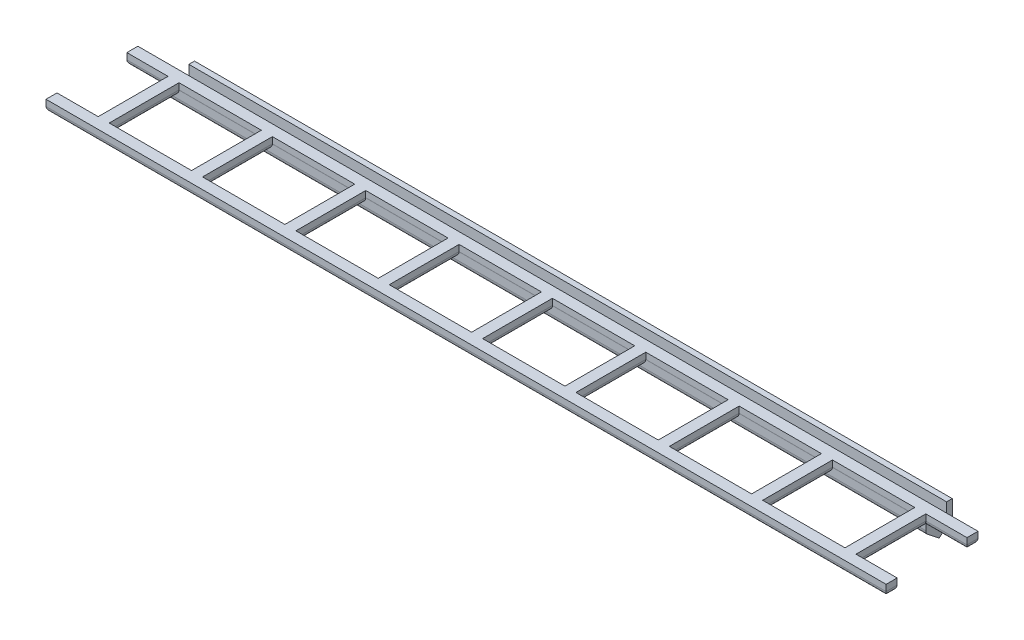
SolidWorks part; units mm, degrees
ref_plane "Front Plane" through (0, 0, 0) normal (0, 0, 1) x (1, 0, 0)
ref_plane "Top Plane" through (0, 0, 0) normal (0, 1, 0) x (1, 0, 0)
ref_plane "Right Plane" through (0, 0, 0) normal (1, 0, 0) x (0, 0, -1)
sketch "Sketch1" plane through (0, 0, 0) normal (0, 1, 0) x (1, 0, 0)
  line L0 (23.5071, 1.4357) -> (23.5071, 4.4357)
  line L1 (12.3071, 1.4357) -> (23.5071, 1.4357)
  line L2 (-1.8929, -17.5643) -> (-1.8929, -20.5643)
  line L3 (9.3071, -17.5643) -> (-1.8929, -17.5643)
  line L4 (12.3071, -17.5643) -> (23.5071, -17.5643)
  line L5 (23.5071, -17.5643) -> (23.5071, -20.5643)
  line L6 (12.3071, 1.4357) -> (12.3071, -17.5643)
  line L7 (9.3071, -17.5643) -> (9.3071, 1.4357)
  line L8 (-1.8929, 4.4357) -> (23.5071, 4.4357)
  line L9 (23.5071, -20.5643) -> (-1.8929, -20.5643)
  line L10 (9.3071, 1.4357) -> (-1.8929, 1.4357)
  line L11 (-1.8929, 1.4357) -> (-1.8929, 4.4357)
  line L12 (48.9071, 1.4357) -> (48.9071, 4.4357)
  line L13 (10.8071, 0) -> (10.8071, 1.5197) construction
  line L14 (0, -8.0643) -> (-1.4046, -8.0643) construction
  line L15 (37.7071, 1.4357) -> (48.9071, 1.4357)
  line L16 (23.5071, -17.5643) -> (23.5071, -20.5643)
  line L17 (34.7071, -17.5643) -> (23.5071, -17.5643)
  line L18 (37.7071, -17.5643) -> (48.9071, -17.5643)
  line L19 (48.9071, -17.5643) -> (48.9071, -20.5643)
  line L20 (37.7071, 1.4357) -> (37.7071, -17.5643)
  line L21 (34.7071, -17.5643) -> (34.7071, 1.4357)
  line L22 (23.5071, 4.4357) -> (48.9071, 4.4357)
  line L23 (48.9071, -20.5643) -> (23.5071, -20.5643)
  line L24 (34.7071, 1.4357) -> (23.5071, 1.4357)
  line L25 (23.5071, 1.4357) -> (23.5071, 4.4357)
  line L26 (74.3071, 1.4357) -> (74.3071, 4.4357)
  line L27 (63.1071, 1.4357) -> (74.3071, 1.4357)
  line L28 (48.9071, -17.5643) -> (48.9071, -20.5643)
  line L29 (60.1071, -17.5643) -> (48.9071, -17.5643)
  line L30 (63.1071, -17.5643) -> (74.3071, -17.5643)
  line L31 (74.3071, -17.5643) -> (74.3071, -20.5643)
  line L32 (63.1071, 1.4357) -> (63.1071, -17.5643)
  line L33 (60.1071, -17.5643) -> (60.1071, 1.4357)
  line L34 (48.9071, 4.4357) -> (74.3071, 4.4357)
  line L35 (74.3071, -20.5643) -> (48.9071, -20.5643)
  line L36 (60.1071, 1.4357) -> (48.9071, 1.4357)
  line L37 (48.9071, 1.4357) -> (48.9071, 4.4357)
  line L38 (99.7071, 1.4357) -> (99.7071, 4.4357)
  line L39 (88.5071, 1.4357) -> (99.7071, 1.4357)
  line L40 (74.3071, -17.5643) -> (74.3071, -20.5643)
  line L41 (85.5071, -17.5643) -> (74.3071, -17.5643)
  line L42 (88.5071, -17.5643) -> (99.7071, -17.5643)
  line L43 (99.7071, -17.5643) -> (99.7071, -20.5643)
  line L44 (88.5071, 1.4357) -> (88.5071, -17.5643)
  line L45 (85.5071, -17.5643) -> (85.5071, 1.4357)
  line L46 (74.3071, 4.4357) -> (99.7071, 4.4357)
  line L47 (99.7071, -20.5643) -> (74.3071, -20.5643)
  line L48 (85.5071, 1.4357) -> (74.3071, 1.4357)
  line L49 (74.3071, 1.4357) -> (74.3071, 4.4357)
  line L50 (125.1071, 1.4357) -> (125.1071, 4.4357)
  line L51 (113.9071, 1.4357) -> (125.1071, 1.4357)
  line L52 (99.7071, -17.5643) -> (99.7071, -20.5643)
  line L53 (110.9071, -17.5643) -> (99.7071, -17.5643)
  line L54 (113.9071, -17.5643) -> (125.1071, -17.5643)
  line L55 (125.1071, -17.5643) -> (125.1071, -20.5643)
  line L56 (113.9071, 1.4357) -> (113.9071, -17.5643)
  line L57 (110.9071, -17.5643) -> (110.9071, 1.4357)
  line L58 (99.7071, 4.4357) -> (125.1071, 4.4357)
  line L59 (125.1071, -20.5643) -> (99.7071, -20.5643)
  line L60 (110.9071, 1.4357) -> (99.7071, 1.4357)
  line L61 (99.7071, 1.4357) -> (99.7071, 4.4357)
  line L62 (150.5071, 1.4357) -> (150.5071, 4.4357)
  line L63 (139.3071, 1.4357) -> (150.5071, 1.4357)
  line L64 (125.1071, -17.5643) -> (125.1071, -20.5643)
  line L65 (136.3071, -17.5643) -> (125.1071, -17.5643)
  line L66 (139.3071, -17.5643) -> (150.5071, -17.5643)
  line L67 (150.5071, -17.5643) -> (150.5071, -20.5643)
  line L68 (139.3071, 1.4357) -> (139.3071, -17.5643)
  line L69 (136.3071, -17.5643) -> (136.3071, 1.4357)
  line L70 (125.1071, 4.4357) -> (150.5071, 4.4357)
  line L71 (150.5071, -20.5643) -> (125.1071, -20.5643)
  line L72 (136.3071, 1.4357) -> (125.1071, 1.4357)
  line L73 (125.1071, 1.4357) -> (125.1071, 4.4357)
  line L74 (175.9071, 1.4357) -> (175.9071, 4.4357)
  line L75 (164.7071, 1.4357) -> (175.9071, 1.4357)
  line L76 (150.5071, -17.5643) -> (150.5071, -20.5643)
  line L77 (161.7071, -17.5643) -> (150.5071, -17.5643)
  line L78 (164.7071, -17.5643) -> (175.9071, -17.5643)
  line L79 (175.9071, -17.5643) -> (175.9071, -20.5643)
  line L80 (164.7071, 1.4357) -> (164.7071, -17.5643)
  line L81 (161.7071, -17.5643) -> (161.7071, 1.4357)
  line L82 (150.5071, 4.4357) -> (175.9071, 4.4357)
  line L83 (175.9071, -20.5643) -> (150.5071, -20.5643)
  line L84 (161.7071, 1.4357) -> (150.5071, 1.4357)
  line L85 (150.5071, 1.4357) -> (150.5071, 4.4357)
  line L86 (201.3071, 1.4357) -> (201.3071, 4.4357)
  line L87 (190.1071, 1.4357) -> (201.3071, 1.4357)
  line L88 (175.9071, -17.5643) -> (175.9071, -20.5643)
  line L89 (187.1071, -17.5643) -> (175.9071, -17.5643)
  line L90 (190.1071, -17.5643) -> (201.3071, -17.5643)
  line L91 (201.3071, -17.5643) -> (201.3071, -20.5643)
  line L92 (190.1071, 1.4357) -> (190.1071, -17.5643)
  line L93 (187.1071, -17.5643) -> (187.1071, 1.4357)
  line L94 (175.9071, 4.4357) -> (201.3071, 4.4357)
  line L95 (201.3071, -20.5643) -> (175.9071, -20.5643)
  line L96 (187.1071, 1.4357) -> (175.9071, 1.4357)
  line L97 (175.9071, 1.4357) -> (175.9071, 4.4357)
  line L98 (226.7071, 1.4357) -> (226.7071, 4.4357)
  line L99 (215.5071, 1.4357) -> (226.7071, 1.4357)
  line L100 (201.3071, -17.5643) -> (201.3071, -20.5643)
  line L101 (212.5071, -17.5643) -> (201.3071, -17.5643)
  line L102 (215.5071, -17.5643) -> (226.7071, -17.5643)
  line L103 (226.7071, -17.5643) -> (226.7071, -20.5643)
  line L104 (215.5071, 1.4357) -> (215.5071, -17.5643)
  line L105 (212.5071, -17.5643) -> (212.5071, 1.4357)
  line L106 (201.3071, 4.4357) -> (226.7071, 4.4357)
  line L107 (226.7071, -20.5643) -> (201.3071, -20.5643)
  line L108 (212.5071, 1.4357) -> (201.3071, 1.4357)
  line L109 (201.3071, 1.4357) -> (201.3071, 4.4357)
  line L110 (23.5071, 1.4357) -> (48.9071, 1.4357) construction
  dimension "D1" = 3
  dimension "D2" = 25
  dimension "D3" = 3
  dimension "D4" = 25.4
  dimension "D6" = 25.4
  dimension "D5" = 9
extrude "Boss-Extrude1" add sketch "Sketch1" along normal blind 3 contours L8 L0 L1 L6 L4 L5 L9 L2 L3 L7 L10 L11 | L21 L24 L25 L22 L12 L15 L20 L18 L19 L23 L16 L17 | L33 L36 L37 L34 L26 L27 L32 L30 L31 L35 L28 L29 | L45 L48 L49 L46 L38 L39 L44 L42 L43 L47 L40 L41 | L56 L54 L55 L59 L52 L53 L57 L60 L61 L58 L50 L51 | L68 L66 L67 L71 L64 L65 L69 L72 L73 L70 L62 L63 | L81 L84 L85 L82 L74 L75 L80 L78 L79 L83 L76 L77 | L93 L96 L97 L94 L86 L87 L92 L90 L91 L95 L88 L89 | L105 L108 L109 L106 L98 L99 L104 L102 L103 L107 L100 L101
fillet "Fillet2" radius 1.3 44 edges at (23.5071, 0, 17.5643) (12.3071, 0, 8.0643) (23.5071, 0, -1.4357) (34.7071, 0, 8.0643) (37.7071, 0, 8.0643) (48.9071, 0, -1.4357) (60.1071, 0, 8.0643) (48.9071, 0, 17.5643) (63.1071, 0, 8.0643) (74.3071, 0, -1.4357) (85.5071, 0, 8.0643) (74.3071, 0, 17.5643) (88.5071, 0, 8.0643) (99.7071, 0, -1.4357) (110.9071, 0, 8.0643) (99.7071, 0, 17.5643) (125.1071, 0, 17.5643) (113.9071, 0, 8.0643) (125.1071, 0, -1.4357) (136.3071, 0, 8.0643) (150.5071, 0, 17.5643) (139.3071, 0, 8.0643) (150.5071, 0, -1.4357) (161.7071, 0, 8.0643) (164.7071, 0, 8.0643) (175.9071, 0, -1.4357) (187.1071, 0, 8.0643) (175.9071, 0, 17.5643) (190.1071, 0, 8.0643) (201.3071, 0, -1.4357) (212.5071, 0, 8.0643) (201.3071, 0, 17.5643) (221.1071, 0, 17.5643) (215.5071, 0, 8.0643) (221.1071, 0, -1.4357) (226.7071, 0, -2.9357) (112.4071, 0, -4.4357) (-1.8929, 0, -2.9357) (3.7071, 0, -1.4357) (9.3071, 0, 8.0643) (3.7071, 0, 17.5643) (-1.8929, 0, 19.0643) (112.4071, 0, 20.5643) (226.7071, 0, 19.0643)
sketch "Sketch2" plane through (215.5071, 0, 0) normal (1, 0, 0) x (0, 0, -1)
  line L0 (1.4357, 1.3) -> (4.4357, 1.3) construction
  line L1 (2.9357, 1.3) -> (1.4366, 1.3)
  line L2 (-17.5643, 1.3) -> (1.4357, 1.3) construction
  line L3 (2.0131, -2.1421) -> (5.0355, -4.5035)
  line L4 (5.0355, -4.5035) -> (8.25, -1.9919)
  line L5 (8.6344, -1.6917) -> (7.0988, -1.6917) construction
  line L6 (2.9357, -0.6917) -> (2.9357, 1.3)
  line L7 (1.4366, -0.9601) -> (1.4366, 1.3)
  line L8 (1.4366, -1.6917) -> (8.6344, -1.6917) construction
  line L9 (5.0355, -1.6917) -> (5.0355, -4.5035) construction
  line L10 (6.0988, -1.6917) -> (3.9357, -1.6917)
  line L11 (7.0988, -0.6917) -> (7.0988, 3)
  line L12 (7.0988, 3) -> (8.6344, 3)
  line L13 (8.6344, 3) -> (8.6344, -1.2039)
  line L14 (1.4357, 3) -> (4.4357, 3) construction
  line L15 (2.9357, -0.6917) -> (3.9357, -1.6917)
  line L16 (7.0988, -0.6917) -> (6.0988, -1.6917)
  arc A1 (8.25, -1.9919) -> (8.6344, -1.2039) centre (7.6344, -1.2039) ccw
  arc A3 (2.0131, -2.1421) -> (1.4366, -0.9601) centre (2.9366, -0.9601) cw
  dimension "D2" = 1
  dimension "D4" = 1.5
extrude "Boss-Extrude2" add sketch "Sketch2" against normal up to surface (206.2 mm away) up to face at (9.3071, 2.15, 8.0643)
equation "\"D6@Sketch1\"=\"D4@Sketch1\""
equation "\"D5@Sketch1\"=int( 9in/\"D4@Sketch1\")"
